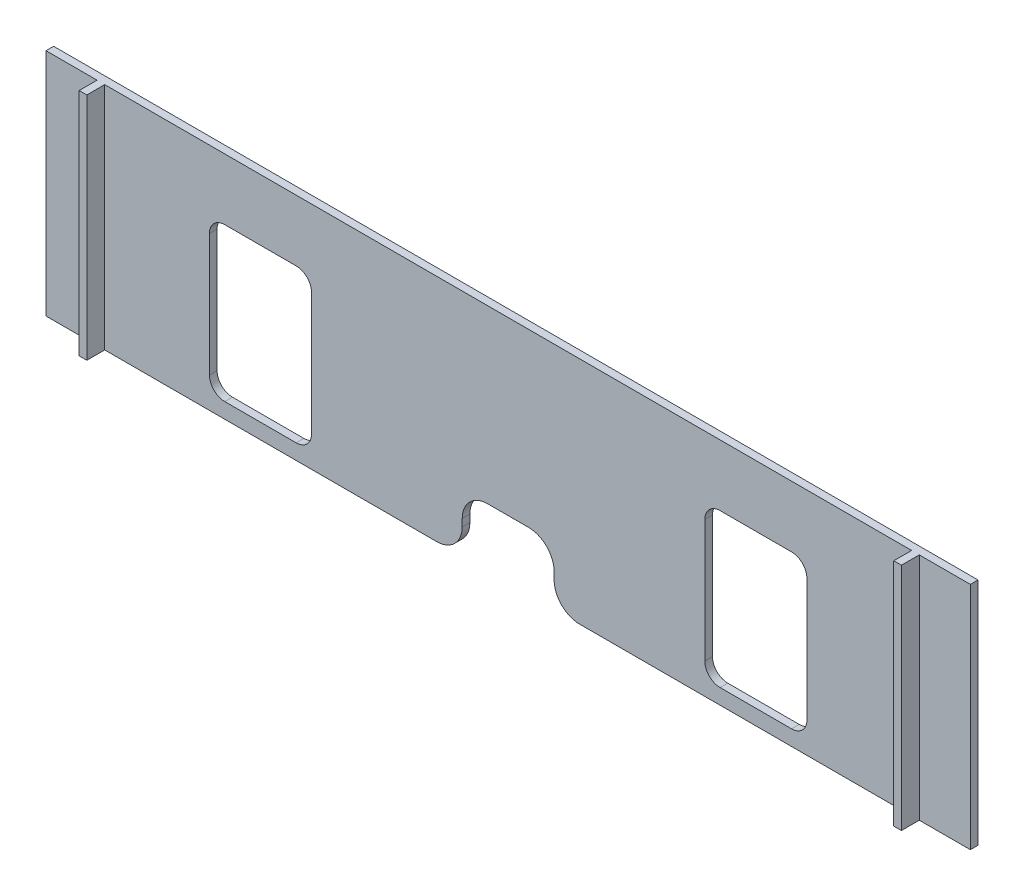
SolidWorks part; units mm, degrees
ref_plane "前视基准面" through (0, 0, 0) normal (0, 0, 1) x (1, 0, 0)
ref_plane "上视基准面" through (0, 0, 0) normal (0, 1, 0) x (1, 0, 0)
ref_plane "右视基准面" through (0, 0, 0) normal (1, 0, 0) x (0, 0, -1)
other "Configuration Table"
sketch "草图1" plane through (0, 0, 0) normal (0, 0, 1) x (1, 0, 0)
  line L1 (-90.5, -22.5) -> (90.5, -22.5)
  line L2 (-90.5, -22.5) -> (-90.5, 22.5)
  line L3 (-90.5, 22.5) -> (90.5, 22.5)
  line L4 (90.5, -22.5) -> (90.5, 22.5)
  line L5 (-90.5, -22.5) -> (90.5, 22.5) construction
  line L6 (-90.5, 22.5) -> (90.5, -22.5) construction
  point P0 (0, 0)
  dimension "D1" = 45
  dimension "D2" = 181
extrude "凸台-拉伸1" add sketch "草图1" along normal blind 1.5
sketch "草图2" plane through (0, 0, 0) normal (0, 0, -1) x (-1, 0, 0)
  line L0 (0, 21.2342) -> (0, -26.0921) construction
  line L2 (-9, -11.0921) -> (9, -11.0921)
  line L3 (9, -11.0921) -> (9, -26.0921)
  line L5 (-9, -26.0921) -> (9, -26.0921)
  line L6 (38.5, -19.5) -> (58.5, -19.5)
  line L7 (58.5, -19.5) -> (58.5, 10.5)
  line L8 (58.5, 10.5) -> (38.5, 10.5)
  line L9 (38.5, 10.5) -> (38.5, -19.5)
  line L10 (-58.5, -19.5) -> (-58.5, 10.5)
  line L11 (-38.5, -19.5) -> (-58.5, -19.5)
  line L12 (-38.5, 10.5) -> (-38.5, -19.5)
  line L13 (-9, -11.0921) -> (-9, -26.0921)
  line L14 (-58.5, 10.5) -> (-38.5, 10.5)
  line L17 (90.5, 22.5) -> (90.5, -22.5) construction
  line L18 (-90.5, 22.5) -> (90.5, 22.5) construction
  point P2 (0, 21.2342)
  point P3 (0, 0)
  dimension "D1" = 32
  dimension "D2" = 20
  dimension "D3" = 30
  dimension "D4" = 12
  dimension "D5" = 18
  dimension "D6" = 15
extrude "切除-拉伸2" cut sketch "草图2" against normal through all
fillet "圆角1" radius 5 2 edges at (-9, -22.5, 0.75) (9, -22.5, 0.75)
fillet "圆角2" radius 5 2 edges at (-9, -11.0921, 0.75) (9, -11.0921, 0.75)
fillet "圆角3" radius 3 8 edges at (38.5, 10.5, 0.75) (58.5, 10.5, 0.75) (58.5, -19.5, 0.75) (38.5, -19.5, 0.75) (-58.5, 10.5, 0.75) (-58.5, -19.5, 0.75) (-38.5, -19.5, 0.75) (-38.5, 10.5, 0.75)
sketch "草图3" plane through (0, 0, 0) normal (0, 0, -1) x (-1, 0, 0)
  line L0 (80.5, 22.5) -> (80.5, -29.3744) construction
  line L1 (80.5, 22.5) -> (80.5, -22.5)
  line L2 (80.5, -22.5) -> (79, -22.5)
  line L3 (79, -22.5) -> (79, 22.5)
  line L4 (79, 22.5) -> (80.5, 22.5)
  line L5 (0, -11.0921) -> (0, 22.5) construction
  line L6 (-79, 22.5) -> (-80.5, 22.5)
  line L7 (-79, -22.5) -> (-79, 22.5)
  line L8 (9, -16.0921) -> (9, -17.5)
  line L9 (14, -22.5) -> (90.5, -22.5)
  line L10 (90.5, -22.5) -> (90.5, 22.5)
  line L11 (90.5, 22.5) -> (-90.5, 22.5)
  line L12 (-90.5, 22.5) -> (-90.5, -22.5)
  line L13 (-90.5, -22.5) -> (-14, -22.5)
  line L14 (-9, -17.5) -> (-9, -16.0921)
  line L15 (-4, -11.0921) -> (4, -11.0921)
  line L16 (9, -16.0921) -> (9, -17.5)
  line L17 (14, -22.5) -> (90.5, -22.5)
  line L18 (90.5, -22.5) -> (90.5, 22.5)
  line L19 (90.5, 22.5) -> (-90.5, 22.5)
  line L20 (-90.5, 22.5) -> (-90.5, -22.5)
  line L21 (-90.5, -22.5) -> (-14, -22.5)
  line L22 (-9, -17.5) -> (-9, -16.0921)
  line L23 (-4, -11.0921) -> (4, -11.0921)
  line L24 (-80.5, -22.5) -> (-79, -22.5)
  line L25 (-80.5, 22.5) -> (-80.5, -22.5)
  arc A4 (9, -17.5) -> (14, -22.5) centre (14, -17.5) ccw
  arc A5 (-14, -22.5) -> (-9, -17.5) centre (-14, -17.5) ccw
  arc A6 (-4, -11.0921) -> (-9, -16.0921) centre (-4, -16.0921) ccw
  arc A7 (9, -16.0921) -> (4, -11.0921) centre (4, -16.0921) ccw
  arc A8 (9, -17.5) -> (14, -22.5) centre (14, -17.5) ccw
  arc A9 (-14, -22.5) -> (-9, -17.5) centre (-14, -17.5) ccw
  arc A10 (-4, -11.0921) -> (-9, -16.0921) centre (-4, -16.0921) ccw
  arc A11 (9, -16.0921) -> (4, -11.0921) centre (4, -16.0921) ccw
  dimension "D2" = 1.5
  dimension "D1" = 0
extrude "凸台-拉伸2" add sketch "草图3" against normal blind 5 contours L1 L2 L3 L4 | L25 L24 L7 L6
